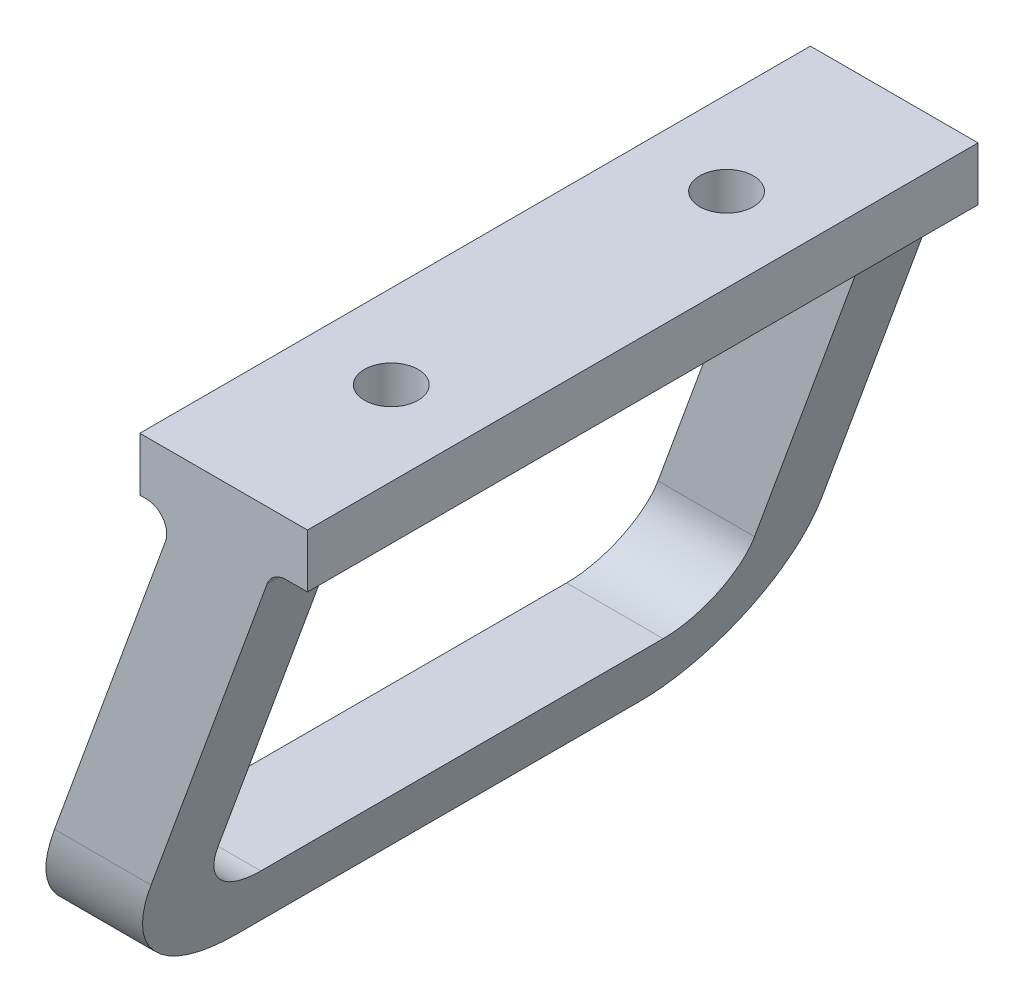
SolidWorks part; units mm, degrees
ref_plane "Front Plane" through (0, 0, 0) normal (0, 0, 1) x (1, 0, 0)
ref_plane "Top Plane" through (0, 0, 0) normal (0, 1, 0) x (1, 0, 0)
ref_plane "Right Plane" through (0, 0, 0) normal (1, 0, 0) x (0, 0, -1)
sketch "Sketch1" plane through (0, 0, 0) normal (0, 0, 1) x (1, 0, 0)
  line L0 (-11.4844, 0) -> (-12.5, 0)
  line L1 (-12.5, 0) -> (-12.5, 8)
  line L2 (-12.5, 8) -> (12.5, 8)
  line L3 (12.5, 8) -> (12.5, 0)
  line L4 (12.5, 0) -> (9.3006, 0)
  line L5 (6.4815, -1.9739) -> (-18.1, -69.5112)
  line L6 (-18.1, -69.5112) -> (-32.5, -69.5112)
  line L7 (-32.5, -69.5112) -> (-8.6654, -4.0261)
  arc A0 (9.3006, 0) -> (6.4815, -1.9739) centre (9.3006, -3) ccw
  arc A1 (-11.4844, 0) -> (-8.6654, -4.0261) centre (-11.4844, -3) cw
  point P9 (0, 8)
  point P15 (7.2, 0)
  point P18 (-7.2, 0)
  dimension "D7" = 3
  dimension "D1" = 5.3
  dimension "D2" = 8
  dimension "D3" = 25
  dimension "D4" = 19.7
  dimension "D5" = 45
  dimension "D6" = 20
extrude "Boss-Extrude1" add sketch "Sketch1" along normal mid plane 100
sketch "Sketch2" plane through (0, 0, 0) normal (1, 0, 0) x (0, 0, -1)
  line L0 (40, -7) -> (-40, -7)
  line L1 (-40, -7) -> (-40, -49.5112)
  line L2 (-30, -59.5112) -> (30, -59.5112)
  line L3 (40, -49.5112) -> (40, -7)
  line L4 (-50, 8) -> (50, 8) construction
  line L5 (-50, -69.5112) -> (50, -69.5112) construction
  line L6 (-50, -69.5112) -> (-50, -1.9739) construction
  line L7 (-50, -69.5112) -> (50, -69.5112) construction
  line L8 (-50, -49.5112) -> (-50, -69.5112)
  line L9 (-50, -69.5112) -> (-30, -69.5112)
  line L10 (0, -69.5112) -> (0, 0) construction
  line L11 (50, -49.5112) -> (50, -69.5112)
  line L12 (50, -69.5112) -> (30, -69.5112)
  arc A0 (-40, -49.5112) -> (-30, -59.5112) centre (-30, -49.5112) ccw
  arc A1 (30, -59.5112) -> (40, -49.5112) centre (30, -49.5112) ccw
  arc A2 (-50, -49.5112) -> (-30, -69.5112) centre (-30, -49.5112) ccw
  arc A3 (50, -49.5112) -> (30, -69.5112) centre (30, -49.5112) cw
  point P10 (0, -7)
  dimension "D1" = 10
  dimension "D5" = 20
  dimension "D2" = 15
  dimension "D3" = 80
  dimension "D4" = 10
extrude "Cut-Extrude1" cut sketch "Sketch2" against normal through all both and the other way through all
sketch "Sketch3" plane through (0, 8, 0) normal (0, 1, 0) x (1, 0, 0)
  line L0 (12.5, -50) -> (12.5, 50) construction
  line L1 (12.5, -50) -> (-12.5, -50) construction
  circle A0 centre (0, -25) radius 4
  circle A1 centre (0, 25) radius 4
  dimension "D2" = 25
  dimension "D4" = 8
  dimension "D1" = 12.5
  dimension "D3" = 50
extrude "Cut-Extrude2" cut sketch "Sketch3" against normal up to surface (15 mm away) and the other way through all up to face at (-2.5478, -7, 0)
